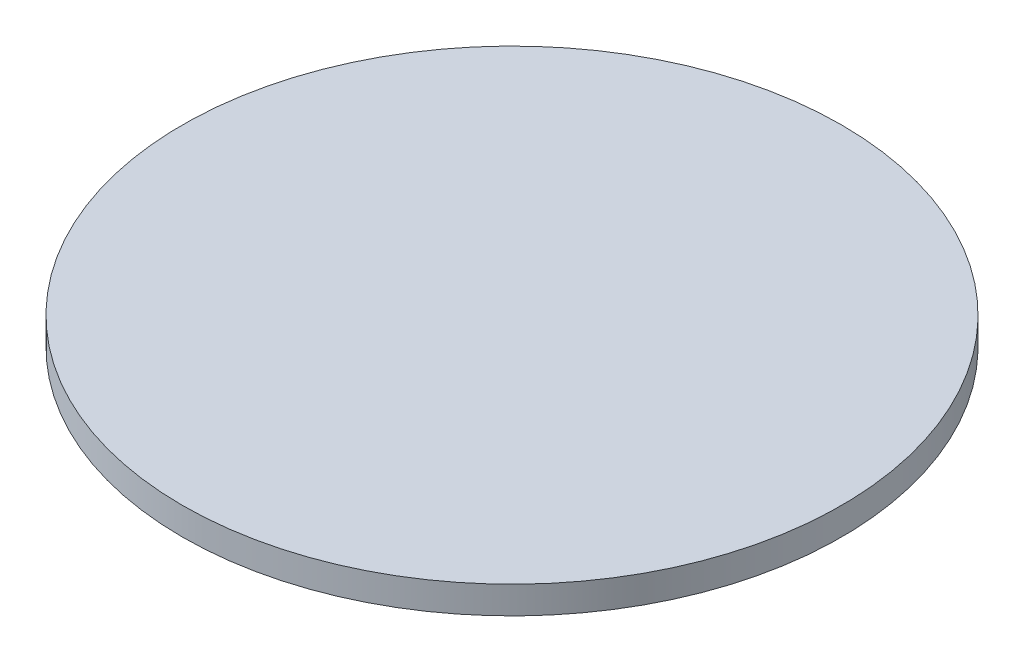
SolidWorks part; units mm, degrees
ref_plane "Front" through (0, 0, 0) normal (0, 0, 1) x (1, 0, 0)
ref_plane "Top" through (0, 0, 0) normal (0, 1, 0) x (1, 0, 0)
ref_plane "Right" through (0, 0, 0) normal (1, 0, 0) x (0, 0, -1)
sketch "Sketch1" plane through (0, 0, 0) normal (0, 1, 0) x (1, 0, 0)
  circle A0 centre (0, 0) radius 12000
  dimension "D1" = 24000
extrude "Boss-Extrude1" add sketch "Sketch1" along normal blind 1000
equation "\"Radius\" = 12"
equation "\"diameter\"=24"
equation "\"D1@Sketch1\"=\"diameter\""
equation "\"height\"=1"
equation "\"D1@Boss-Extrude1\"=\"height\""
